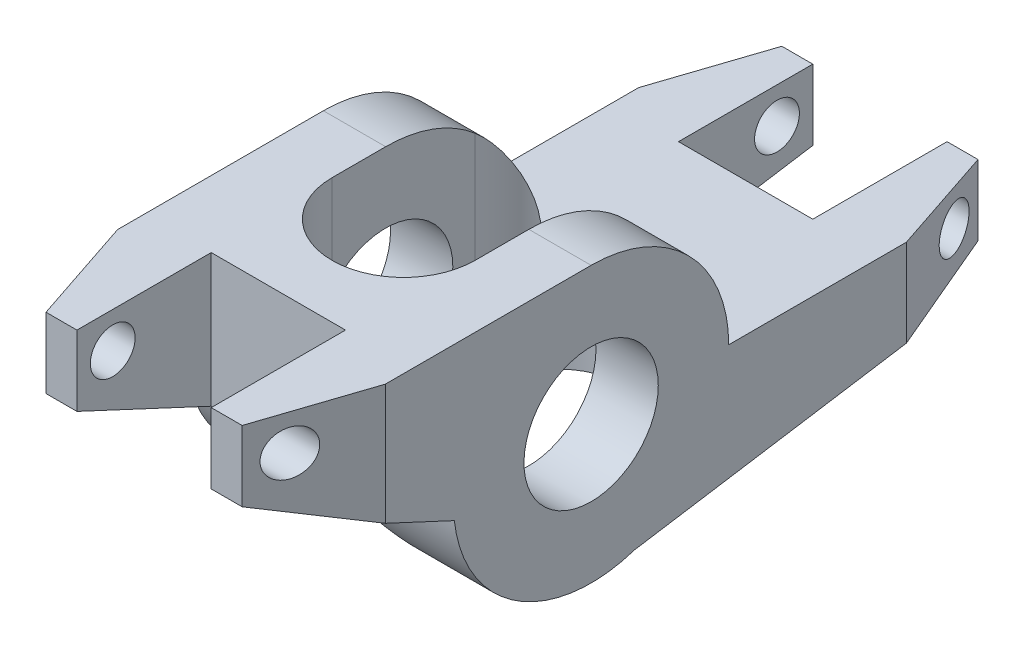
SolidWorks part; units mm, degrees
ref_plane "Front Plane" through (0, 0, 0) normal (0, 0, 1) x (1, 0, 0)
ref_plane "Top Plane" through (0, 0, 0) normal (0, 1, 0) x (1, 0, 0)
ref_plane "Right Plane" through (0, 0, 0) normal (1, 0, 0) x (0, 0, -1)
sketch "Sketch1" plane through (0, 0, 0) normal (1, 0, 0) x (0, 0, -1)
  line L0 (0, 9.765) -> (-22.225, 9.765)
  line L1 (-22.225, 9.765) -> (-22.225, 4.765)
  line L2 (-22.225, 4.765) -> (-9.7059, -1.0728)
  line L3 (9.765, 0) -> (29.995, 0)
  line L4 (29.995, 0) -> (29.995, -5)
  line L5 (29.995, -5) -> (3.0856, -9.2647)
  circle A0 centre (0, 0) radius 4.765
  arc A1 (-9.7059, -1.0728) -> (3.0856, -9.2647) centre (0, 0) ccw
  circle A2 centre (0, 0) radius 9.765 construction
  arc A3 (9.765, 0) -> (0, 9.765) centre (0, 0) ccw
  dimension "D1" = 9.53
  dimension "D3" = 22.225
  dimension "D4" = 5
  dimension "D5" = 25
  dimension "D6" = 20.23
  dimension "D7" = 5
  dimension "D2" = 5
extrude "Boss-Extrude1" add sketch "Sketch1" along normal mid plane 19
chamfer "Chamfer1" distance 2.54 distance2 7.62 2 edges at (9.5, -2.5, -29.995) (9.5, 7.265, 22.225)
chamfer "Chamfer2" distance 7.62 distance2 2.54 2 edges at (-9.5, 7.265, 22.225) (-9.5, -2.5, -29.995)
sketch "Sketch2" plane through (0, 0, 0) normal (0, 1, 0) x (1, 0, 0)
  line L0 (0, -3.81) -> (0, 6.35) construction
  line L1 (-5.08, -3.81) -> (-5.08, 6.35)
  line L2 (5.08, -3.81) -> (5.08, 6.35)
  arc A0 (-5.08, -3.81) -> (5.08, -3.81) centre (0, -3.81) ccw
  arc A1 (5.08, 6.35) -> (-5.08, 6.35) centre (0, 6.35) ccw
  point P3 (0, 1.27)
  dimension "D1" = 10.16
  dimension "D2" = 10.16
  dimension "D3" = 3.81
extrude "Cut-Extrude1" cut sketch "Sketch2" against normal mid plane 49
sketch "Sketch3" plane through (0, 0, 0) normal (0, 1, 0) x (1, 0, 0)
  line L0 (6.96, 29.995) -> (-6.96, 29.995) construction
  line L1 (4.765, 20.465) -> (-4.765, 20.465)
  line L2 (4.765, 20.465) -> (4.765, 29.995)
  line L3 (4.765, 29.995) -> (-4.765, 29.995)
  line L4 (-4.765, 20.465) -> (-4.765, 29.995)
  line L5 (4.765, 20.465) -> (-4.765, 29.995) construction
  line L6 (4.765, 29.995) -> (-4.765, 20.465) construction
  line L7 (6.96, -22.225) -> (-6.96, -22.225) construction
  line L8 (-4.765, -12.695) -> (4.765, -12.695)
  line L9 (-4.765, -12.695) -> (-4.765, -22.225)
  line L10 (-4.765, -22.225) -> (4.765, -22.225)
  line L11 (4.765, -12.695) -> (4.765, -22.225)
  line L12 (-4.765, -12.695) -> (4.765, -22.225) construction
  line L13 (-4.765, -22.225) -> (4.765, -12.695) construction
  point P0 (0, 25.23)
  point P7 (0, -17.46)
  dimension "D1" = 9.53
  dimension "D2" = 9.53
  dimension "D3" = 9.53
  dimension "D4" = 9.53
extrude "Cut-Extrude2" cut sketch "Sketch3" against normal mid plane 49
sketch "Sketch4" plane through (0, 0, 0) normal (1, 0, 0) x (0, 0, -1)
  line L0 (22.375, 0) -> (29.995, 0) construction
  line L1 (29.995, 0) -> (29.995, -5) construction
  line L2 (-22.225, 9.765) -> (-14.605, 9.765) construction
  line L3 (-22.225, 4.765) -> (-22.225, 9.765) construction
  circle A0 centre (-19.685, 7.225) radius 1.59
  circle A1 centre (27.455, -2.54) radius 1.59
  dimension "D1" = 3.18
  dimension "D3" = 2.54
  dimension "D2" = 2.54
  dimension "D4" = 2.54
  dimension "D5" = 2.54
extrude "Cut-Extrude3" cut sketch "Sketch4" against normal mid plane 49
